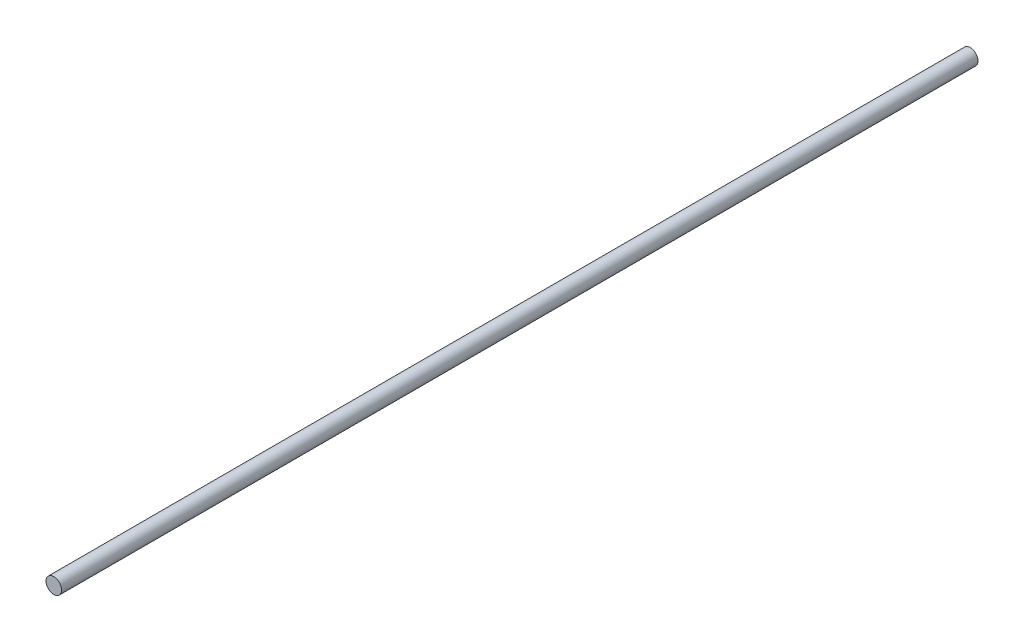
SolidWorks part; units mm, degrees
ref_plane "前视基准面" through (0, 0, 0) normal (0, 0, 1) x (1, 0, 0)
ref_plane "上视基准面" through (0, 0, 0) normal (0, 1, 0) x (1, 0, 0)
ref_plane "右视基准面" through (0, 0, 0) normal (1, 0, 0) x (0, 0, -1)
sketch "草图1" plane through (0, 0, 0) normal (0, 0, 1) x (1, 0, 0)
  circle A0 centre (0, 0) radius 1.25
  dimension "D1" = 2.5
extrude "凸台-拉伸1" add sketch "草图1" against normal up to surface (147 mm away) from surface
